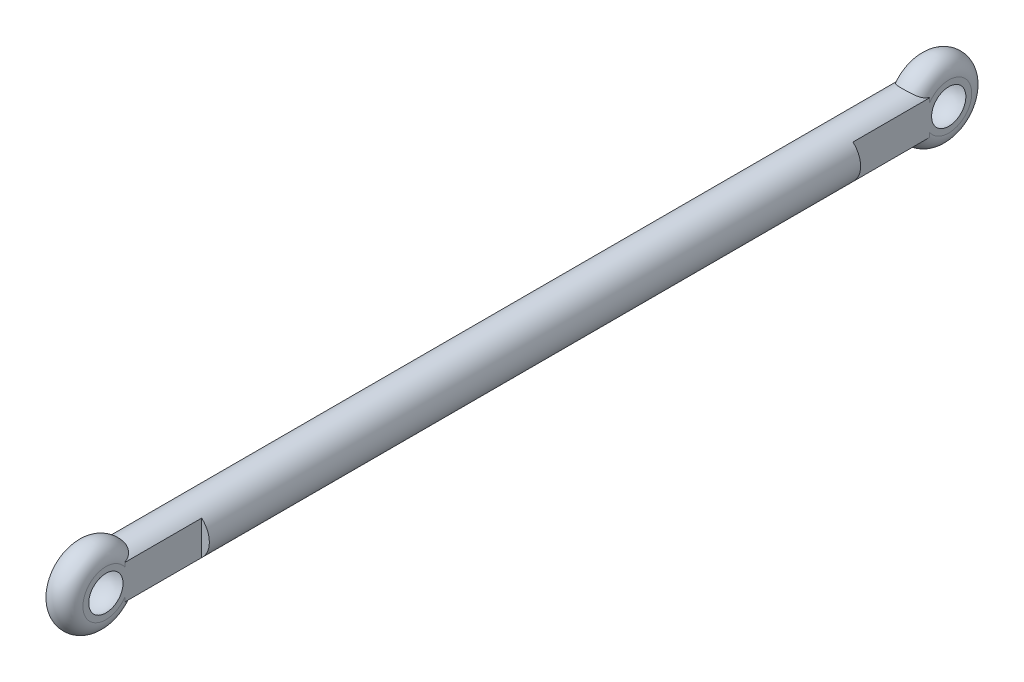
SolidWorks part; units mm, degrees
ref_plane "前视基准面" through (0, 0, 0) normal (0, 0, 1) x (1, 0, 0)
ref_plane "上视基准面" through (0, 0, 0) normal (0, 1, 0) x (1, 0, 0)
ref_plane "右视基准面" through (0, 0, 0) normal (1, 0, 0) x (0, 0, -1)
sketch "草图1" plane through (0, 0, 0) normal (0, 0, 1) x (1, 0, 0)
  circle A0 centre (0, 0) radius 3
  dimension "D1" = 6
extrude "凸台-拉伸1" add sketch "草图1" along normal mid plane 85
sketch "草图2" plane through (0, 0, 42.5) normal (0, 0, 1) x (1, 0, 0)
  line L0 (-2, 2.2361) -> (-2, -2.2361)
  line L1 (2, 2.2361) -> (2, -2.2361)
  circle A1 centre (0, 0) radius 3
  circle A2 centre (0, 0) radius 3
  circle M4 centre (0, 0) radius 3
  dimension "D2" = 4
  dimension "D3" = 2
  dimension "D1" = 0
extrude "凸台-拉伸2" add sketch "草图2" along normal blind 10 contours L1 L0 M4
ref_plane "基准面1" through (0, 0, 55) normal (0, 0, 1) x (1, 0, 0)
sketch "草图3" plane through (0, 0, 55) normal (0, 0, 1) x (1, 0, 0)
  line L0 (0, 0) -> (5.0711, 0) construction
  line L1 (-2, 3) -> (-2, 0)
  line L4 (-2, 0) -> (2, 0)
  line L6 (2, 0) -> (2, 3)
  arc A0 (2, 3) -> (-2, 3) centre (0, 3) ccw
  dimension "D2" = 4
  dimension "D1" = 3
revolve "旋转1" add sketch "草图3" angle 360 about L0
sketch "草图4" plane through (0, 0, 55) normal (0, 0, 1) x (1, 0, 0)
  line L0 (-3.4682, 0) -> (4.4651, 0) construction
  line L1 (-3, 0) -> (3, 0)
  arc A0 (3, 0) -> (-3, 0) centre (0, 0) ccw
revolve "切除-旋转1" cut sketch "草图4" angle 360 about L0
mirror "镜向1" about plane through (0, 0, 0) normal (0, 0, 1) of "切除-旋转1", "旋转1", "凸台-拉伸2"
